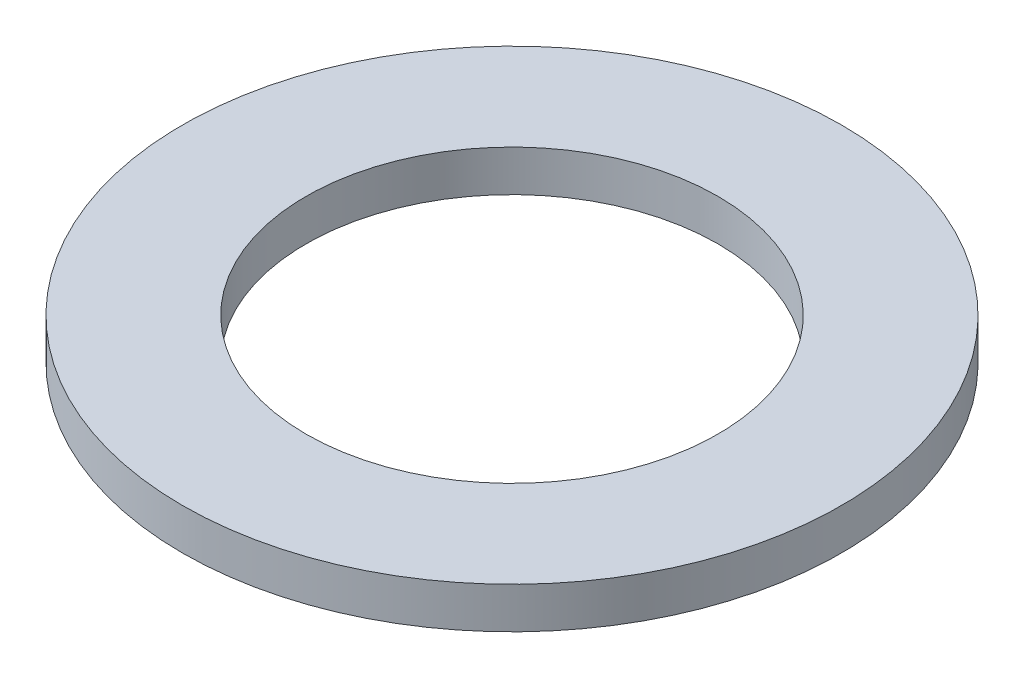
SolidWorks part; units mm, degrees
ref_plane "Front Plane" through (0, 0, 0) normal (0, 0, 1) x (1, 0, 0)
ref_plane "Top Plane" through (0, 0, 0) normal (0, 1, 0) x (1, 0, 0)
ref_plane "Right Plane" through (0, 0, 0) normal (1, 0, 0) x (0, 0, -1)
sketch "Sketch1" plane through (0, 0, 0) normal (0, 1, 0) x (1, 0, 0)
  circle A0 centre (0, 0) radius 8
  dimension "OD" = 16
extrude "Boss-Extrude1" add sketch "Sketch1" along normal blind 1
sketch "Sketch5" plane through (0, 1, 0) normal (0, 1, 0) x (-1, 0, 0)
  circle A0 centre (0, 0) radius 5
  dimension "ID" = 10
extrude "Cut-Extrude1" cut sketch "Sketch5" against normal through all
